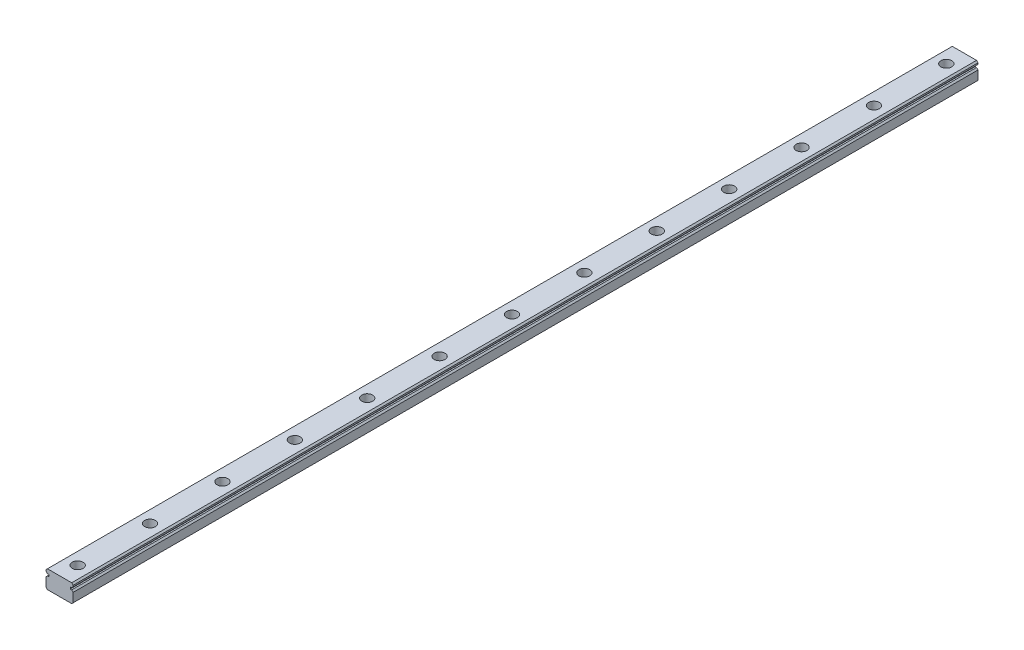
SolidWorks part; units mm, degrees
ref_plane "Front" through (0, 0, 0) normal (0, 0, 1) x (1, 0, 0)
ref_plane "Top" through (0, 0, 0) normal (0, 1, 0) x (1, 0, 0)
ref_plane "Right" through (0, 0, 0) normal (1, 0, 0) x (0, 0, -1)
sketch "Sketch1" plane through (0, 0, 0) normal (0, 0, 1) x (1, 0, 0)
  line L0 (6.7, 5) -> (-6.7, 5)
  line L1 (-7.5, -5) -> (7.5, -5) construction
  line L2 (-7.5, -5) -> (-7.5, 5) construction
  line L3 (-7.5, 5) -> (7.5, 5) construction
  line L4 (7.5, -5) -> (7.5, 5) construction
  line L5 (-7.5, -5) -> (7.5, 5) construction
  line L6 (-7.5, 5) -> (7.5, -5) construction
  line L7 (-7.5, 4.2) -> (-7.5, 3.4)
  line L8 (-6.7, 2.6) -> (-5.9, 2.6)
  line L9 (-5.9, 2.6) -> (-5.9, 1.6)
  line L10 (-5.9, 1.6) -> (-6.7, 1.6)
  line L11 (-7.5, 0.8) -> (-7.5, -4.2)
  line L12 (-6.7, -5) -> (6.7, -5)
  line L13 (-6.7, 5) -> (-7.5, 4.2)
  line L14 (-6.7, 1.6) -> (-7.5, 0.8)
  line L15 (-7.5, -4.2) -> (-6.7, -5)
  line L16 (-7.5, 3.4) -> (-6.7, 2.6)
  line L17 (0, -5) -> (0, 5) construction
  line L18 (7.5, -5) -> (7.5, 5) construction
  line L19 (7.5, 3.4) -> (6.7, 2.6)
  line L20 (7.5, -4.2) -> (6.7, -5)
  line L21 (6.7, 1.6) -> (7.5, 0.8)
  line L22 (6.7, 5) -> (7.5, 4.2)
  line L23 (7.5, 0.8) -> (7.5, -4.2)
  line L24 (5.9, 1.6) -> (6.7, 1.6)
  line L25 (5.9, 2.6) -> (5.9, 1.6)
  line L26 (6.7, 2.6) -> (5.9, 2.6)
  line L27 (7.5, 4.2) -> (7.5, 3.4)
  point P0 (0, 0)
  point P8 (-7.5, 2.6)
  point P9 (-7.5, 1.6)
  point P30 (7.5, 1.6)
  point P31 (7.5, 2.6)
  dimension "D1" = 10
  dimension "D2" = 15
  dimension "D3" = 2.4
  dimension "D4" = 1
  dimension "D9" = 0.8
extrude "Boss-Extrude1" add sketch "Sketch1" along normal blind 500
sketch "Sketch4" plane through (0, 5, 0) normal (0, 1, 0) x (1, 0, 0)
  line L0 (0, 0) -> (0, -10) construction
  line L1 (6.7, 0) -> (-6.7, 0) construction
  circle A0 centre (0, -10) radius 3
  dimension "D2" = 6
  dimension "D1" = 10
extrude "Cut-Extrude1" cut sketch "Sketch4" against normal blind 4.5 contours A0
sketch "Sketch6" plane through (0, 0.5, 0) normal (0, 1, 0) x (1, 0, 0)
  circle A0 centre (0, -10) radius 1.75
  dimension "D1" = 3.5
extrude "Cut-Extrude2" cut sketch "Sketch6" against normal through all
pattern_linear "LPattern1" count 13 spacing 40 along (0, 0, 1) of "Cut-Extrude2", "Cut-Extrude1"
